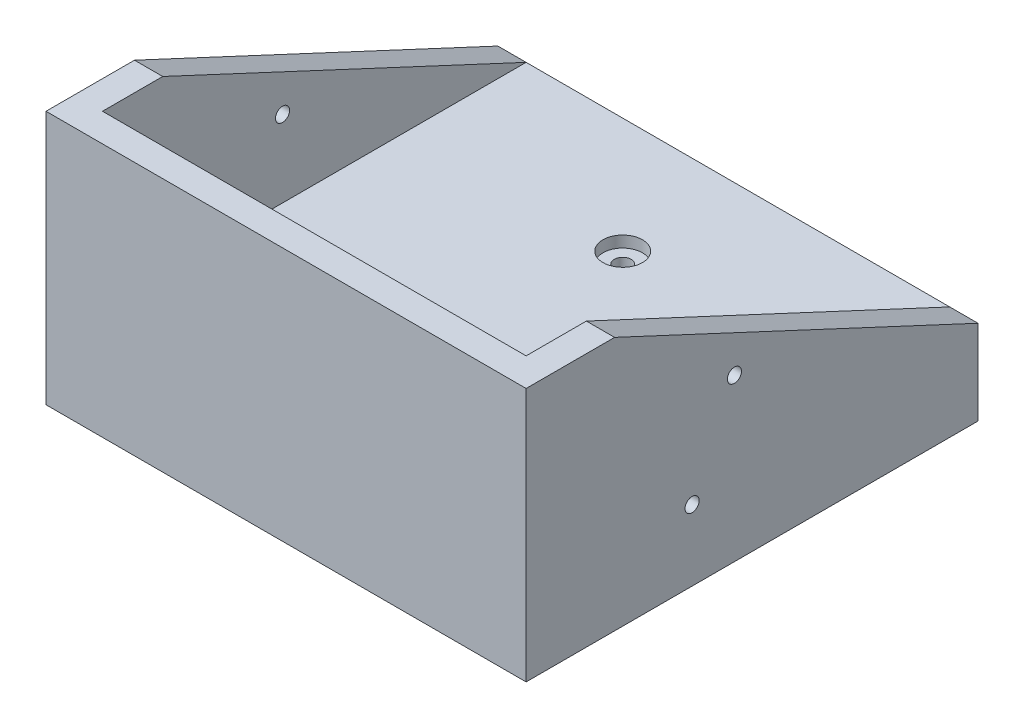
SolidWorks part; units mm, degrees
ref_plane "Front Plane" through (0, 0, 0) normal (0, 0, 1) x (1, 0, 0)
ref_plane "Top Plane" through (0, 0, 0) normal (0, 1, 0) x (1, 0, 0)
ref_plane "Right Plane" through (0, 0, 0) normal (1, 0, 0) x (0, 0, -1)
sketch "Sketch1" plane through (0, 0, 0) normal (0, 1, 0) x (1, 0, 0)
  line L1 (42.5, 40) -> (-42.5, 40)
  line L2 (42.5, 40) -> (42.5, -40)
  line L3 (42.5, -40) -> (-42.5, -40)
  line L4 (-42.5, 40) -> (-42.5, -40)
  line L5 (42.5, 40) -> (-42.5, -40) construction
  line L6 (42.5, -40) -> (-42.5, 40) construction
  point P0 (0, 0)
  dimension "D1" = 85
  dimension "D2" = 80
extrude "Boss-Extrude1" add sketch "Sketch1" along normal blind 5
sketch "Sketch2" plane through (0, 0, 0) normal (0, -1, 0) x (1, 0, 0)
  line L0 (0, 0) -> (29, 0) construction
  line L1 (-29, -23.5) -> (29, -23.5) construction
  line L2 (-29, -23.5) -> (-29, 23.5) construction
  line L3 (-29, 23.5) -> (29, 23.5) construction
  line L4 (29, -23.5) -> (29, 23.5) construction
  line L5 (-29, -23.5) -> (29, 23.5) construction
  line L6 (-29, 23.5) -> (29, -23.5) construction
  circle A0 centre (0, 19.6) radius 1.5
  circle A1 centre (0, -19.6) radius 1.5
  point P0 (0, 0)
  point P10 (0, 0)
  dimension "D4" = 3
  dimension "D1" = 47
  dimension "D2" = 58
  dimension "D5" = 39.2
extrude "Cut-Extrude1" cut sketch "Sketch2" against normal through all
sketch "Sketch3" plane through (0, 0, 0) normal (0, -1, 0) x (1, 0, 0)
  line L4 (32, -11) -> (-29.5, -11) construction
  line L5 (29.5, -17) -> (32, -17)
  line L7 (29.5, -5) -> (32, -5)
  line L8 (29.5, -24) -> (29.5, 24)
  line L9 (-29.5, -24) -> (29.5, -24)
  line L10 (-29.5, 24) -> (-29.5, -24)
  line L11 (29.5, 24) -> (-29.5, 24)
  line L12 (29.5, -24) -> (29.5, -17)
  line L13 (-29.5, -24) -> (29.5, -24)
  line L14 (-29.5, 24) -> (-29.5, -24)
  line L15 (29.5, 24) -> (-29.5, 24)
  line L16 (32, -17) -> (32, -5)
  line L17 (29.5, -5) -> (29.5, 24)
  line L22 (-42.5, 40) -> (-42.5, -40)
  line L23 (-42.5, -40) -> (42.5, -40)
  line L24 (42.5, -40) -> (42.5, 40)
  line L25 (42.5, 40) -> (-42.5, 40)
  line L26 (-42.5, 40) -> (-42.5, -40)
  line L27 (-42.5, -40) -> (42.5, -40)
  line L28 (42.5, -40) -> (42.5, 40)
  line L29 (42.5, 40) -> (-42.5, 40)
  dimension "D2" = 12
  dimension "D3" = 13
  dimension "D4" = 2.5
  dimension "D1" = 0.5
  dimension "D5" = 0
sketch "Sketch4" plane through (0, 5, 0) normal (0, 1, 0) x (1, 0, 0)
  line L0 (42.5, 40) -> (-42.5, 40) construction
  line L2 (-42.5, -40) -> (-42.5, 40)
  line L3 (-42.5, 40) -> (-37.5, 40)
  line L4 (-37.5, -35) -> (-37.5, 40)
  line L5 (-37.5, -35) -> (37.5, -35)
  line L6 (42.5, -40) -> (-42.5, -40)
  line L7 (42.5, -40) -> (42.5, 40)
  line L8 (42.5, 40) -> (37.5, 40)
  line L9 (37.5, -35) -> (37.5, 40)
  line L10 (-42.5, -40) -> (42.5, -40) construction
  dimension "D1" = 5
  dimension "D2" = 5
extrude "Boss-Extrude3" add sketch "Sketch4" along normal blind 30
sketch "Sketch5" plane through (0, 5, 0) normal (0, 1, 0) x (1, 0, 0)
  circle A5 centre (0, 19.6) radius 3.5
  circle A6 centre (0, 19.6) radius 3.5
  circle A8 centre (0, -19.6) radius 3.5
  circle A9 centre (0, -19.6) radius 3.5
  dimension "D1" = 2
  dimension "D2" = 2
extrude "Cut-Extrude2" cut sketch "Sketch5" against normal blind 2
sketch "Sketch6" plane through (-42.5, 0, 0) normal (-1, 0, 0) x (0, 0, 1)
  line L0 (3.1231, 18.5911) -> (10.6246, 2.5042) construction
  line L1 (6.8738, 10.5476) -> (25, 19) construction
  line L4 (40, 35) -> (40, 0) construction
  line L5 (24.3352, 35) -> (-40, 5)
  line L6 (-40, 35) -> (40, 35) construction
  line L7 (-40, 35) -> (-40, 0) construction
  line L8 (-40, 5) -> (-40, 35)
  line L9 (-40, 35) -> (24.3352, 35)
  line L10 (40, 0) -> (-40, 0) construction
  circle A0 centre (10.6246, 2.5042) radius 1.25
  circle A1 centre (3.1231, 18.5911) radius 1.25
  dimension "D2" = 2.5
  dimension "D1" = 17.75
  dimension "D3" = 20
  dimension "D4" = 19
  dimension "D5" = 25
  dimension "D6" = 15
extrude "Cut-Extrude3" cut sketch "Sketch6" against normal through all
extrude "Boss-Extrude4" add sketch "Sketch3" along normal blind 10
sketch "Sketch7" plane through (42.5, 0, 0) normal (1, 0, 0) x (0, 0, -1)
  line L0 (-26.6925, 32.6436) -> (27.0515, 7.5823)
  line L1 (26.265, 1.1633) -> (21.6162, -8.8061)
  line L2 (17.2045, -13.5346) -> (-36.5395, 11.5266)
  line L3 (-38.7162, 17.5068) -> (-36.9623, 21.268)
  line L4 (-36.9623, 21.268) -> (-41.4938, 23.3811)
  line L5 (-41.4938, 23.3811) -> (-38.9581, 28.8189)
  line L6 (-38.9581, 28.8189) -> (-34.4266, 26.7058)
  line L7 (-34.4266, 26.7058) -> (-32.6727, 30.467)
  line L8 (17.2045, -13.5346) -> (19.8036, -7.9608)
  line L9 (19.8036, -7.9608) -> (21.6162, -8.8061)
  line L11 (-6.8738, 10.5476) -> (-25, 19) construction
  line L12 (-6.8738, 10.5476) -> (-25, 19) construction
  line L13 (-29.9235, 8.4415) -> (-20.0765, 29.5585) construction
  line L15 (27.0515, 7.5823) -> (24.4524, 2.0085)
  line L16 (24.4524, 2.0085) -> (26.265, 1.1633)
  arc A0 (-36.5395, 11.5266) -> (-38.7162, 17.5068) centre (-34.6378, 15.605) cw
  arc A1 (-26.6925, 32.6436) -> (-32.6727, 30.467) centre (-28.5943, 28.5652) ccw
  dimension "D5" = 4.5
  dimension "D1" = 23.3
  dimension "D2" = 11.8
  dimension "D3" = 6
  dimension "D4" = 5
  dimension "D6" = 52
  dimension "D7" = 54
  dimension "D8" = 11
